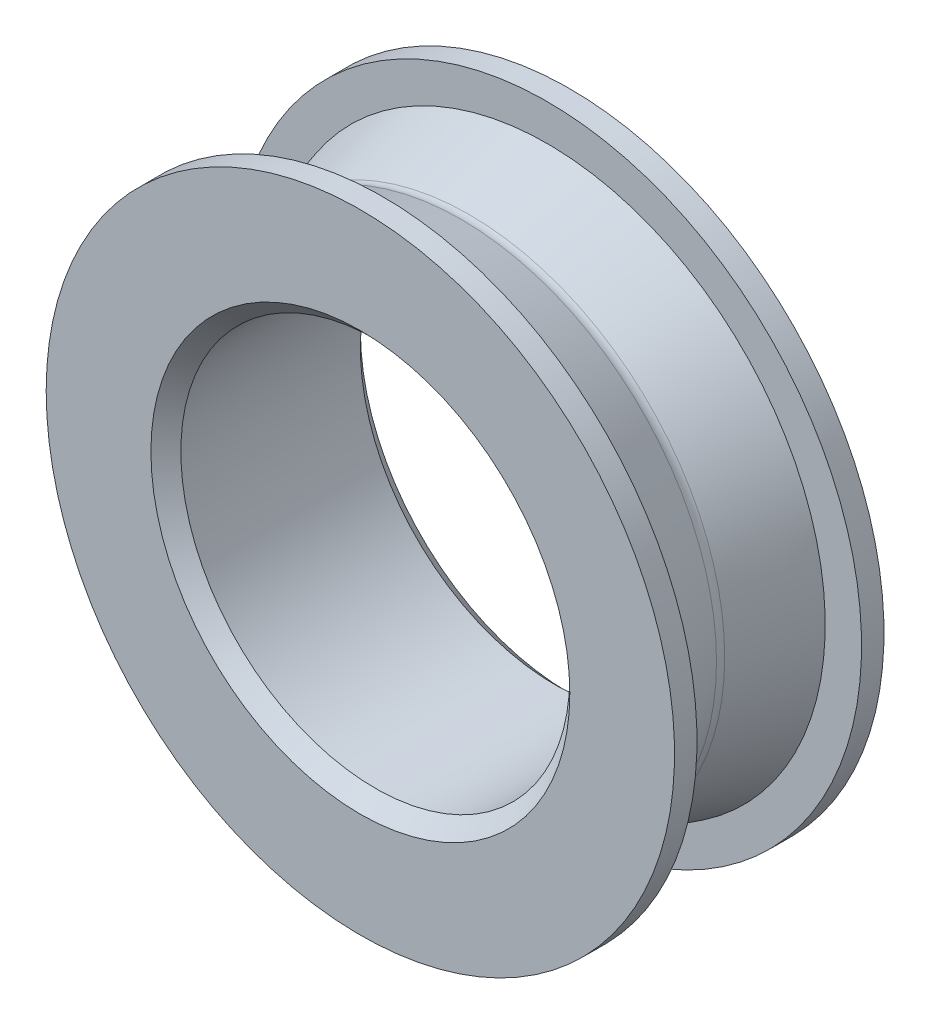
SolidWorks part; units mm, degrees
material "ABS"
ref_plane "Front Plane" through (0, 0, 0) normal (0, 0, 1) x (1, 0, 0)
ref_plane "Top Plane" through (0, 0, 0) normal (0, 1, 0) x (1, 0, 0)
ref_plane "Right Plane" through (0, 0, 0) normal (1, 0, 0) x (0, 0, -1)
sketch "Sketch1" plane through (0, 0, 0) normal (0, 0, 1) x (1, 0, 0)
  circle A0 centre (0, 0) radius 13
  circle A1 centre (0, 0) radius 19
  dimension "D1" = 26
  dimension "D2" = 6
extrude "Boss-Extrude1" add sketch "Sketch1" along normal blind 14
sketch "Sketch2" plane through (0, 0, 0) normal (0, 1, 0) x (1, 0, 0)
  line L0 (-19, 0) -> (-17, -7)
  line L1 (-17, -7) -> (-19, -14)
  line L2 (-19, -14) -> (-19, 0)
  line L3 (-19, -7) -> (-10.8102, -7) construction
  line L4 (0, 0) -> (0, -14) construction
  line L5 (-19, -14) -> (19, -14) construction
  dimension "D1" = 2
revolve "Cut-Revolve1" cut sketch "Sketch2" angle 360 about L4
sketch "Sketch3" plane through (0, 0, 0) normal (0, 0, -1) x (-1, 0, 0)
  circle A1 centre (0, 0) radius 13
  circle A2 centre (0, 0) radius 21
  circle A3 centre (0, 0) radius 19 construction
  dimension "D1" = 2
  dimension "D2" = 26
extrude "Boss-Extrude2" add sketch "Sketch3" against normal blind 1.5
ref_plane "Plane1" through (0, 0, 7) normal (0, 0, 1) x (1, 0, 0)
mirror "Mirror1" about plane through (0, 0, 7) normal (0, 0, 1) of "Boss-Extrude2"
fillet "Fillet1" radius 1 1 edges at (-17, 0, 7)
chamfer "Chamfer2" distance 1 angle 45 2 edges at (13, 0, 0) (13, 0, 14)
